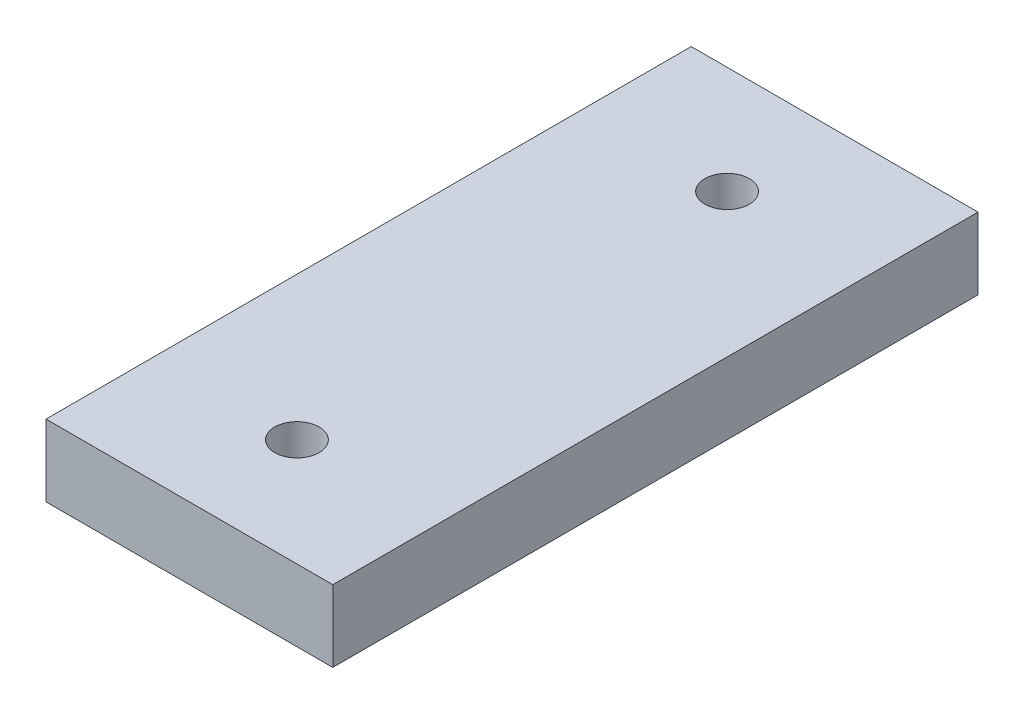
SolidWorks part; units mm, degrees
material "Thornel Mat VMA"
ref_plane "前视基准面" through (0, 0, 0) normal (0, 0, 1) x (1, 0, 0)
ref_plane "上视基准面" through (0, 0, 0) normal (0, 1, 0) x (1, 0, 0)
ref_plane "右视基准面" through (0, 0, 0) normal (1, 0, 0) x (0, 0, -1)
sketch "草图1" plane through (0, 0, 0) normal (0, 1, 0) x (1, 0, 0)
  line L1 (-10, -22.5) -> (10, -22.5)
  line L2 (-10, -22.5) -> (-10, 22.5)
  line L3 (-10, 22.5) -> (10, 22.5)
  line L4 (10, -22.5) -> (10, 22.5)
  line L5 (-10, -22.5) -> (10, 22.5) construction
  line L6 (-10, 22.5) -> (10, -22.5) construction
  point P0 (0, 0)
  dimension "D1" = 45
  dimension "D2" = 20
extrude "凸台-拉伸1" add sketch "草图1" along normal blind 5
sketch "草图2" plane through (0, 5, 0) normal (0, 1, 0) x (1, 0, 0)
  line L0 (0, 22.5) -> (0, -22.5) construction
  line L1 (10, 22.5) -> (-10, 22.5) construction
  line L2 (-10, -22.5) -> (10, -22.5) construction
  line L3 (-10, 0) -> (10, 0) construction
  line L4 (-10, 22.5) -> (-10, -22.5) construction
  line L5 (10, -22.5) -> (10, 22.5) construction
  circle A0 centre (0, 15) radius 1.55
  circle A1 centre (0, -15) radius 1.55
  dimension "D1" = 3.1
  dimension "D2" = 15
extrude "切除-拉伸1" cut sketch "草图2" against normal blind 5
